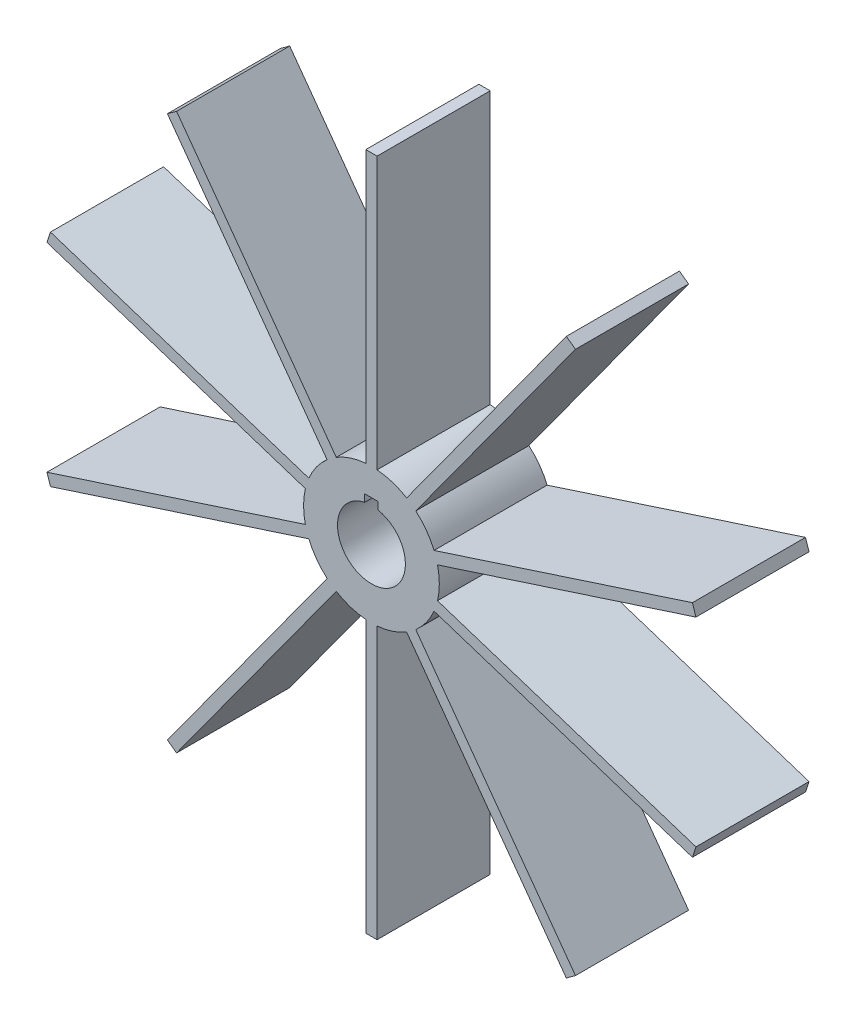
SolidWorks part; units mm, degrees
ref_plane "前视基准面" through (0, 0, 0) normal (0, 0, 1) x (1, 0, 0)
ref_plane "上视基准面" through (0, 0, 0) normal (0, 1, 0) x (1, 0, 0)
ref_plane "右视基准面" through (0, 0, 0) normal (1, 0, 0) x (0, 0, -1)
sketch "草图1" plane through (0, 0, 0) normal (0, 0, 1) x (1, 0, 0)
  circle A0 centre (0, 0) radius 30
  dimension "D1" = 60
extrude "凸台-拉伸1" add sketch "草图1" along normal blind 50
sketch "草图2" plane through (0, 0, 50) normal (0, 0, 1) x (1, 0, 0)
  line L1 (-3, 18) -> (3, 18)
  line L2 (-3, 18) -> (-3, 14.6969)
  line L4 (3, 18) -> (3, 14.6969)
  arc A0 (-3, 14.6969) -> (3, 14.6969) centre (0, 0) ccw
  point P3 (0, 15)
  dimension "D1" = 30
  dimension "D2" = 6
  dimension "D3" = 18
extrude "切除-拉伸1" cut sketch "草图2" against normal through all
ref_plane "基准面1" through (0, 150, 0) normal (0, 1, 0) x (1, 0, 0)
sketch "草图3" plane through (0, 150, 0) normal (0, 1, 0) x (1, 0, 0)
  line L0 (-30, -50) -> (30, -50) construction
  line L1 (-2.5, 0) -> (2.5, 0)
  line L2 (-2.5, 0) -> (-2.5, -50)
  line L3 (-2.5, -50) -> (2.5, -50)
  line L4 (2.5, 0) -> (2.5, -50)
  line L5 (0, -50) -> (0, 0) construction
  line L6 (-2.5, -25) -> (2.5, -25) construction
  line L7 (-30, 0) -> (-30, -50) construction
  line L8 (-30, 0) -> (-30, -50) construction
  line L9 (30, 0) -> (-30, 0) construction
  point P0 (0, -25)
  point P14 (-30, -25)
  dimension "D1" = 5
extrude "凸台-拉伸2" add sketch "草图3" against normal up to surface (120.1043 mm away)
pattern_circular "阵列(圆周)1" count 10 over 360 about axis through (0, 0, 0) along (0, 0, 1) of "凸台-拉伸2"
